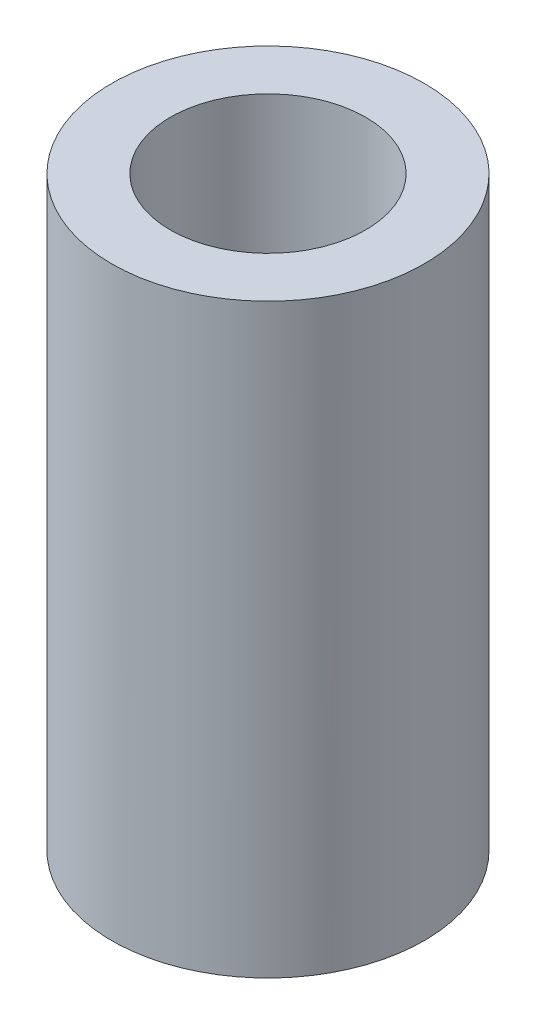
SolidWorks part; units mm, degrees
ref_plane "Front Plane" through (0, 0, 0) normal (0, 0, 1) x (1, 0, 0)
ref_plane "Top Plane" through (0, 0, 0) normal (0, 1, 0) x (1, 0, 0)
ref_plane "Right Plane" through (0, 0, 0) normal (1, 0, 0) x (0, 0, -1)
sketch "Sketch1" plane through (0, 0, 0) normal (0, 1, 0) x (1, 0, 0)
  circle A0 centre (0, 0) radius 16
  circle A1 centre (0, 0) radius 10
  dimension "D1" = 20
  dimension "D2" = 32
extrude "Boss-Extrude1" add sketch "Sketch1" along normal blind 30
sketch "Sketch2" plane through (0, 0, 0) normal (0, -1, 0) x (1, 0, 0)
  circle A0 centre (0, 0) radius 16
extrude "Boss-Extrude2" add sketch "Sketch2" along normal blind 30
sketch "Sketch3" plane through (0, -30, 0) normal (0, -1, 0) x (1, 0, 0)
  circle A0 centre (0, 0) radius 6.5
  dimension "D1" = 13
extrude "Cut-Extrude1" cut sketch "Sketch3" against normal blind 30
sketch "Sketch4" plane through (0, -30, 0) normal (0, -1, 0) x (1, 0, 0)
  line L1 (-1.5, -5.25) -> (1.5, -5.25)
  line L2 (-1.5, -5.25) -> (-1.5, -7.75)
  line L3 (-1.5, -7.75) -> (1.5, -7.75)
  line L4 (1.5, -5.25) -> (1.5, -7.75)
  line L5 (-1.5, -5.25) -> (1.5, -7.75) construction
  line L6 (-1.5, -7.75) -> (1.5, -5.25) construction
  circle A0 centre (0, 0) radius 6.5 construction
  point P0 (0, -6.5)
  dimension "D1" = 3
  dimension "D2" = 2.5
extrude "Cut-Extrude2" cut sketch "Sketch4" against normal blind 30
